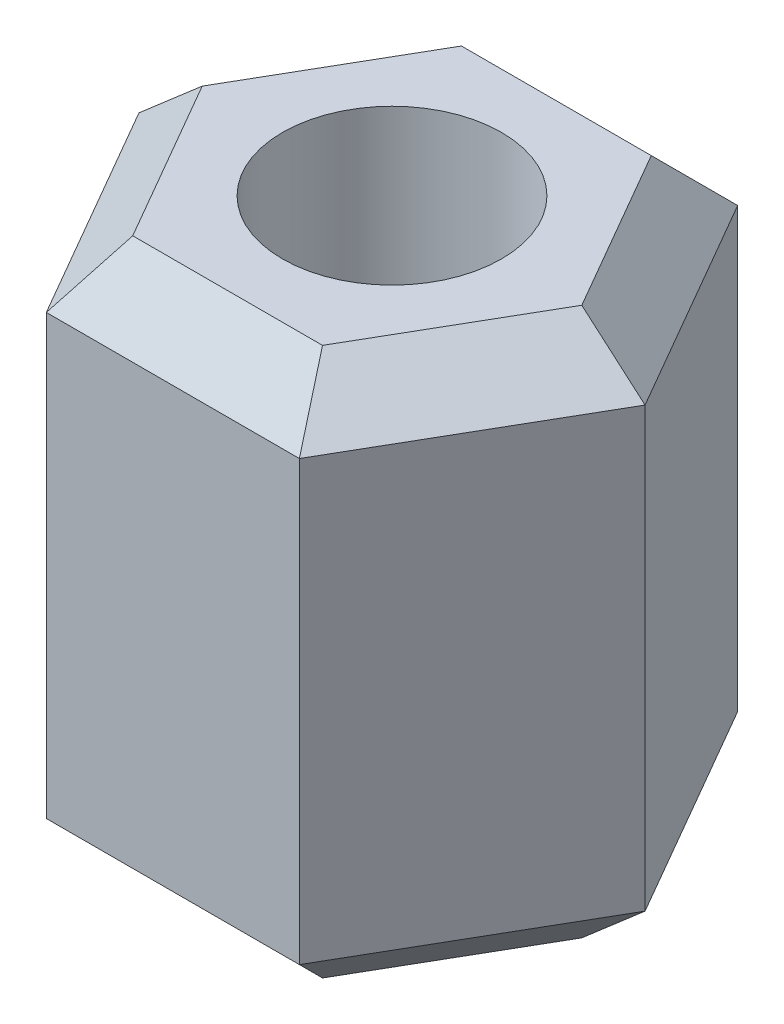
SolidWorks part; units mm, degrees
ref_plane "前视基准面" through (0, 0, 0) normal (0, 0, 1) x (1, 0, 0)
ref_plane "上视基准面" through (0, 0, 0) normal (0, 1, 0) x (1, 0, 0)
ref_plane "右视基准面" through (0, 0, 0) normal (1, 0, 0) x (0, 0, -1)
sketch "草图1" plane through (0, 0, 0) normal (0, 1, 0) x (1, 0, 0)
  line L1 (-2.3094, 0) -> (-1.1547, -2)
  line L2 (-1.1547, -2) -> (1.1547, -2)
  line L3 (1.1547, -2) -> (2.3094, 0)
  line L4 (2.3094, 0) -> (1.1547, 2)
  line L5 (1.1547, 2) -> (-1.1547, 2)
  line L6 (-1.1547, 2) -> (-2.3094, 0)
  circle A0 centre (0, 0) radius 1
  circle A1 centre (0, 0) radius 2 construction
extrude "凸台-拉伸1" add sketch "草图1" along normal blind 5
chamfer "倒角1" distance 0.5 angle 45 12 edges at (1.7321, 0, 1) (0, 0, 2) (-1.7321, 0, 1) (-1.7321, 0, -1) (0, 0, -2) (1.7321, 0, -1) (1.7321, 5, -1) (0, 5, -2) (-1.7321, 5, -1) (-1.7321, 5, 1) (0, 5, 2) (1.7321, 5, 1)
